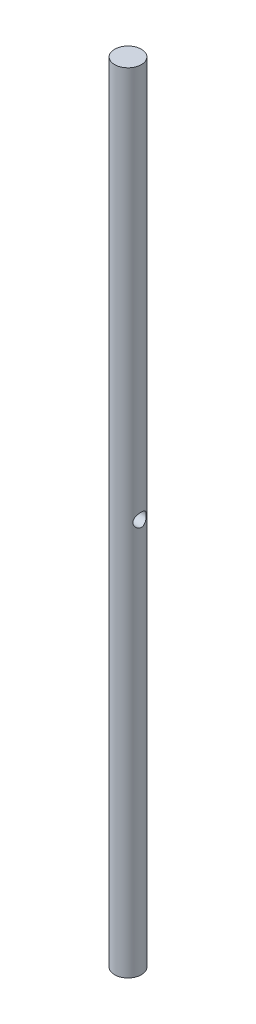
SolidWorks part; units mm, degrees
ref_plane "Front Plane" through (0, 0, 0) normal (0, 0, 1) x (1, 0, 0)
ref_plane "Top Plane" through (0, 0, 0) normal (0, 1, 0) x (1, 0, 0)
ref_plane "Right Plane" through (0, 0, 0) normal (1, 0, 0) x (0, 0, -1)
sketch "Sketch1" plane through (0, 0, 0) normal (0, 1, 0) x (1, 0, 0)
  circle A0 centre (0, 0) radius 1
  dimension "D1" = 2
extrude "Boss-Extrude1" add sketch "Sketch1" along normal blind 59
sketch "Sketch2" plane through (0, 0, 0) normal (1, 0, 0) x (0, 0, -1)
  line L0 (-1, 0) -> (1, 0) construction
  circle A0 centre (0, 29.5) radius 0.5
  dimension "D1" = 1
  dimension "D2" = 29.5
extrude "Cut-Extrude1" cut sketch "Sketch2" against normal through all both and the other way through all
